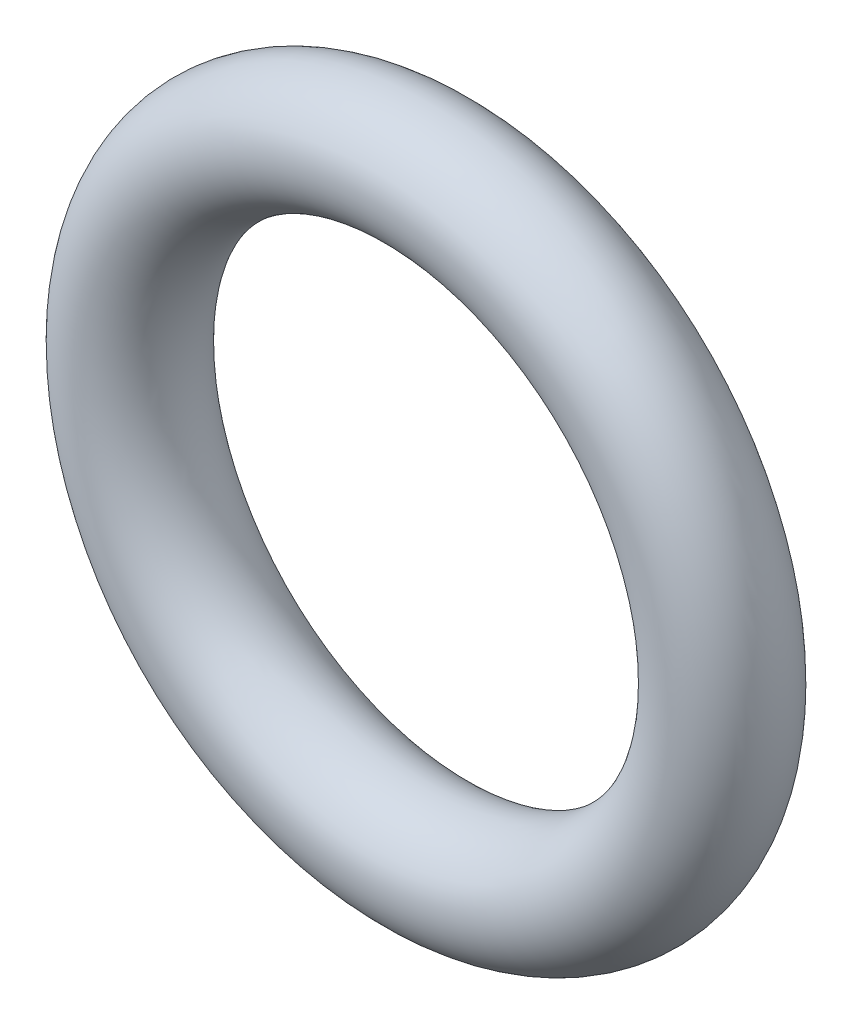
SolidWorks part; units mm, degrees
ref_plane "Front Plane" through (0, 0, 0) normal (0, 0, 1) x (1, 0, 0)
ref_plane "Top Plane" through (0, 0, 0) normal (0, 1, 0) x (1, 0, 0)
ref_plane "Right Plane" through (0, 0, 0) normal (1, 0, 0) x (0, 0, -1)
ref_axis "Axis1" through (0, 0, -75.9247) along (0, 0, 1)
sketch "Sketch1" plane through (0, 0, 0) normal (0, 1, 0) x (1, 0, 0)
  line L0 (-0.4976, 0) -> (0.4976, 0) construction
  line L1 (0, -0.4976) -> (0, 0.4976) construction
  circle A0 centre (-1.25, 0) radius 0.25
  dimension "D1" = 0.5
  dimension "D2" = 1.25
revolve "Revolve1" add sketch "Sketch1" angle 360 about axis through (0, 0, -75.9247) along (0, 0, 1)
